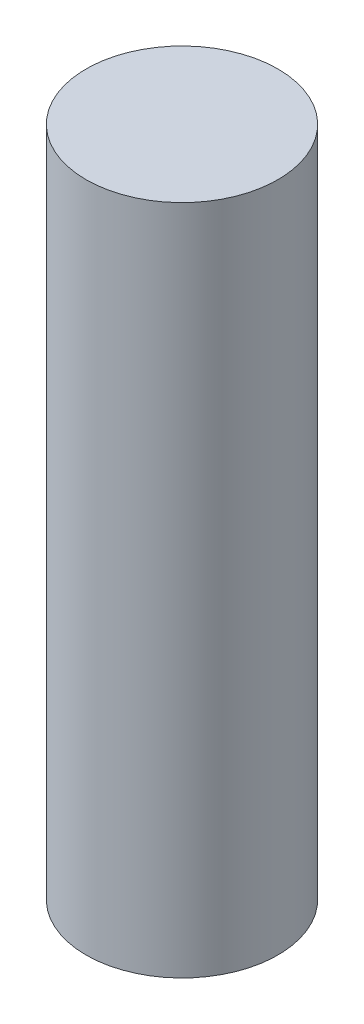
SolidWorks part; units mm, degrees
ref_plane "前视基准面" through (0, 0, 0) normal (0, 0, 1) x (1, 0, 0)
ref_plane "上视基准面" through (0, 0, 0) normal (0, 1, 0) x (1, 0, 0)
ref_plane "右视基准面" through (0, 0, 0) normal (1, 0, 0) x (0, 0, -1)
other "Configuration Table"
sketch "草图1" plane through (0, 0, 0) normal (0, 1, 0) x (1, 0, 0)
  circle A0 centre (0, 0) radius 10
  dimension "D1" = 20
extrude "凸台-拉伸1" add sketch "草图1" along normal blind 70
